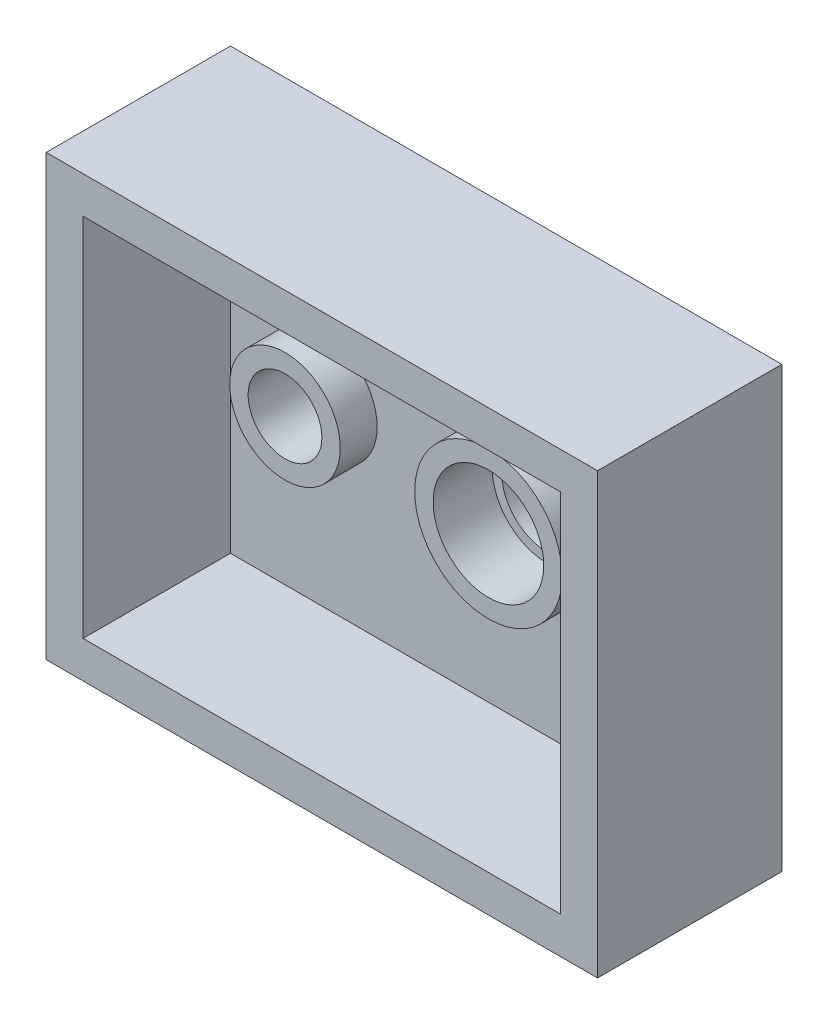
SolidWorks part; units mm, degrees
ref_plane "Front Plane" through (0, 0, 0) normal (0, 0, 1) x (1, 0, 0)
ref_plane "Top Plane" through (0, 0, 0) normal (0, 1, 0) x (1, 0, 0)
ref_plane "Right Plane" through (0, 0, 0) normal (1, 0, 0) x (0, 0, -1)
sketch "Sketch1" plane through (0, 0, 0) normal (0, 0, 1) x (1, 0, 0)
  circle A0 centre (17.526, 0) radius 4.826
  circle A1 centre (0, 0) radius 3.175
  circle A2 centre (0, 0) radius 5.334 construction
  circle A3 centre (17.526, 0) radius 13.208 construction
  dimension "D1" = 6.35
  dimension "D2" = 9.652
  dimension "D4" = 10.668
  dimension "D5" = 26.416
  dimension "D3" = 17.526
sketch "Sketch2" plane through (0, 0, 0) normal (0, 0, 1) x (1, 0, 0)
  line L1 (-11.049, 18.923) -> (36.449, 18.923)
  line L2 (-11.049, 18.923) -> (-11.049, -18.923)
  line L3 (-11.049, -18.923) -> (36.449, -18.923)
  line L4 (36.449, 18.923) -> (36.449, -18.923)
  dimension "D1" = 47.498
  dimension "D2" = 37.846
  dimension "D3" = 11.049
  dimension "D4" = 18.923
extrude "Boss-Extrude1" add sketch "Sketch2" along normal blind 3.175
sketch "Sketch4" plane through (0, 0, 3.175) normal (0, 0, 1) x (1, 0, 0)
  line L8 (-7.874, 15.748) -> (-7.874, -15.748)
  line L9 (-7.874, -15.748) -> (33.274, -15.748)
  line L10 (33.274, -15.748) -> (33.274, 15.748)
  line L11 (33.274, 15.748) -> (-7.874, 15.748)
  line L12 (-7.874, 15.748) -> (-7.874, -15.748)
  line L13 (-7.874, -15.748) -> (33.274, -15.748)
  line L14 (33.274, -15.748) -> (33.274, 15.748)
  line L15 (33.274, 15.748) -> (-7.874, 15.748)
  line M5 (-11.049, 18.923) -> (-11.049, -18.923)
  line M6 (-11.049, -18.923) -> (36.449, -18.923)
  line M7 (36.449, -18.923) -> (36.449, 18.923)
  line M8 (36.449, 18.923) -> (-11.049, 18.923)
  dimension "D1" = 3.175
extrude "Boss-Extrude2" add sketch "Sketch4" along normal blind 12.7 contours L15 L14 L13 L12 M8 M5 M6 M7
sketch "Sketch5" plane through (0, 0, 0) normal (0, 0, -1) x (-1, 0, 0)
  circle A1 centre (0, 0) radius 4.7625
  circle A2 centre (-17.526, 0) radius 6.35
  dimension "D1" = 9.525
  dimension "D2" = 12.7
extrude "Boss-Extrude3" add sketch "Sketch5" against normal blind 6.35
sketch "Sketch6" plane through (0, 0, 6.35) normal (0, 0, 1) x (1, 0, 0)
  circle A0 centre (17.526, 0) radius 4.7625
  circle A1 centre (0, 0) radius 3.175
  dimension "D1" = 9.525
  dimension "D2" = 6.35
extrude "Cut-Extrude1" cut sketch "Sketch6" against normal blind 5.08
sketch "Sketch7" plane through (0, 0, 3.175) normal (0, 0, 1) x (1, 0, 0)
  circle A0 centre (0, 0) radius 1.524
  circle A1 centre (17.526, 0) radius 3.937
  dimension "D1" = 3.048
  dimension "D2" = 7.874
extrude "Cut-Extrude2" cut sketch "Sketch7" against normal through all
equation "\"PD input\"= 0.375in"
equation "\"PD output\"= 1.0000in"
equation "\"center distance\"= ( \"PD input\" + \"PD output\" ) / 2"
equation "\"Bearing OD input\"= 0.250in"
equation "\"Bearing OD output\"= 0.375in"
equation "\"Input bearing circle\"= 0.420in"
equation "\"Output bearing circle\"= 1.040in"
equation "\"Clearence\"= 0.1000in"
equation "\"wall thickness\"= 0.125in"
equation "\"Housing Length\"= ( \"Input bearing circle\" / 2 ) + \"center distance\" + ( \"Output bearing circle\" / 2 ) + 2 * ( \"Clearence\" + \"wall thickness\" )"
equation "\"Housing Width\"= \"Output bearing circle\" + 2 * ( \"Clearence\" + \"wall thickness\" )"
equation "\"0.25n\"=0.2"
